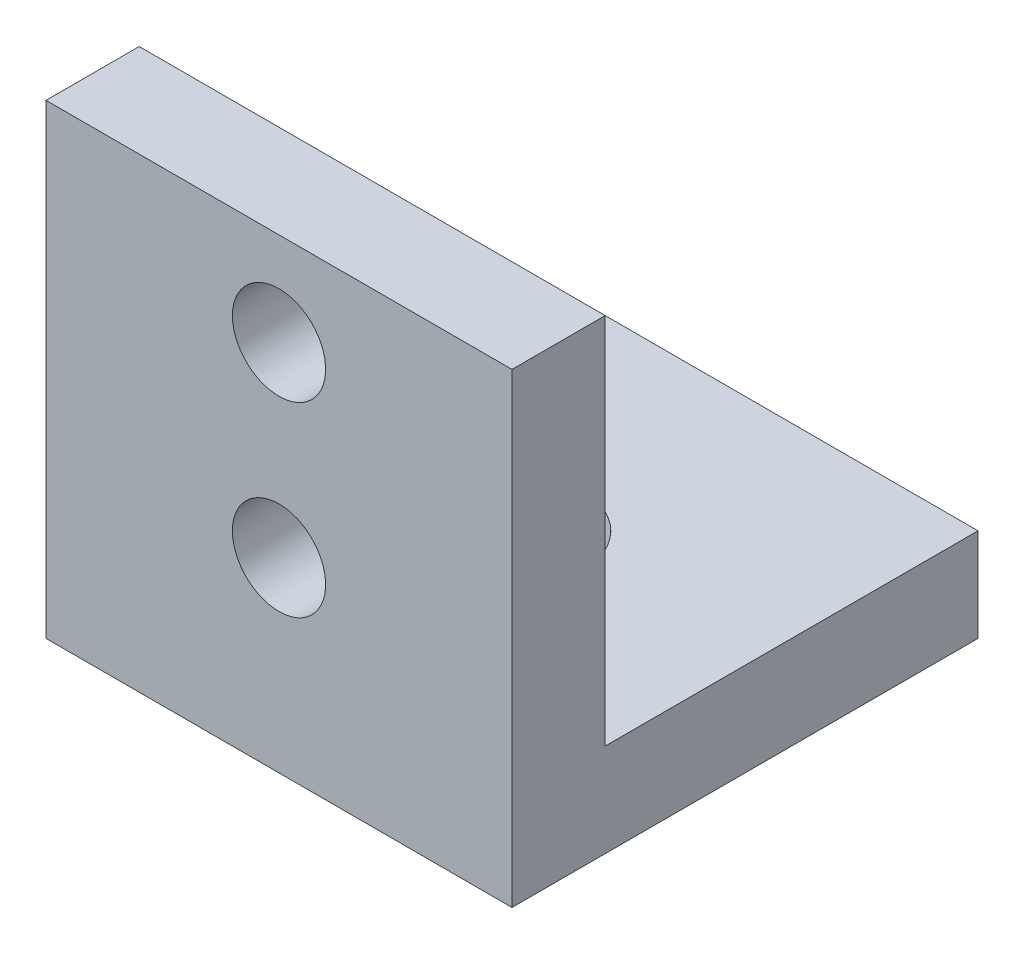
SolidWorks part; units mm, degrees
material "Delrin 2700 NC010, Low Viscosity Acetal Copolymer (SS)"
ref_plane "Front Plane" through (0, 0, 0) normal (0, 0, 1) x (1, 0, 0)
ref_plane "Top Plane" through (0, 0, 0) normal (0, 1, 0) x (1, 0, 0)
ref_plane "Right Plane" through (0, 0, 0) normal (1, 0, 0) x (0, 0, -1)
sketch "Sketch2" plane through (0, 0, 0) normal (0, 1, 0) x (1, 0, 0)
  line L1 (-12.7, -12.7) -> (12.7, -12.7)
  line L2 (-12.7, -12.7) -> (-12.7, 12.7)
  line L3 (-12.7, 12.7) -> (12.7, 12.7)
  line L4 (12.7, -12.7) -> (12.7, 12.7)
  line L5 (-12.7, -12.7) -> (12.7, 12.7) construction
  line L6 (-12.7, 12.7) -> (12.7, -12.7) construction
  circle A0 centre (0, 0) radius 3.81
  dimension "D1" = 7.62
  dimension "D2" = 25.4
  dimension "D3" = 25.4
extrude "Boss-Extrude1" add sketch "Sketch2" along normal blind 5.08
sketch "Sketch3" plane through (0, 5.08, 0) normal (0, 1, 0) x (1, 0, 0)
  line L0 (12.7, -12.7) -> (12.7, 12.7) construction
  line L1 (-12.7, -12.7) -> (12.7, -12.7)
  line L2 (-12.7, -12.7) -> (-12.7, -7.62)
  line L3 (-12.7, -7.62) -> (12.7, -7.62)
  line L4 (12.7, -12.7) -> (12.7, -7.62)
  dimension "D1" = 5.08
extrude "Boss-Extrude2" add sketch "Sketch3" along normal blind 20.32
sketch "Sketch4" plane through (0, 0, 7.62) normal (0, 0, -1) x (-1, 0, 0)
  line L0 (-12.7, 25.4) -> (12.7, 25.4) construction
  line L1 (-12.7, 5.08) -> (12.7, 5.08) construction
  circle A0 centre (0, 20.32) radius 2.54
  circle A1 centre (0, 10.16) radius 2.54
  dimension "D1" = 5.08
  dimension "D2" = 5.08
  dimension "D3" = 5.08
  dimension "D4" = 5.08
extrude "Cut-Extrude1" cut sketch "Sketch4" against normal through all
